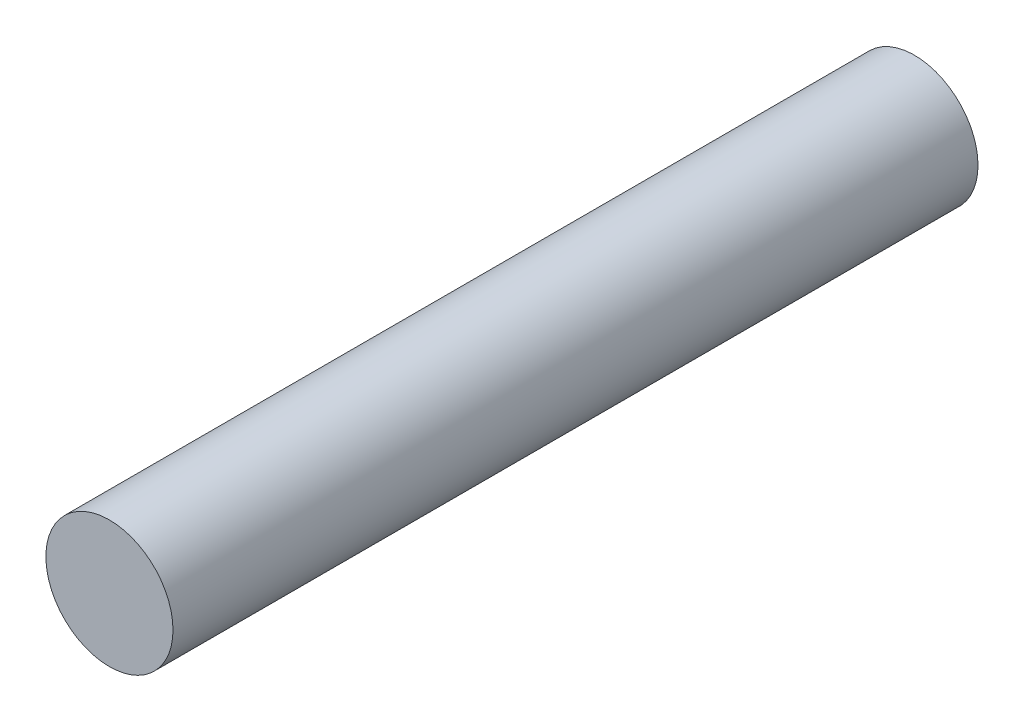
SolidWorks part; units mm, degrees
material "A-1"
ref_plane "Front Plane" through (0, 0, 0) normal (0, 0, 1) x (1, 0, 0)
ref_plane "Top Plane" through (0, 0, 0) normal (0, 1, 0) x (1, 0, 0)
ref_plane "Right Plane" through (0, 0, 0) normal (1, 0, 0) x (0, 0, -1)
sketch "Sketch1" plane through (0, 0, 0) normal (0, 0, 1) x (1, 0, 0)
  circle A0 centre (0, 0) radius 2.3813
  dimension "D1" = 4.7625
extrude "Boss-Extrude1" add sketch "Sketch1" against normal mid plane 30.1625
